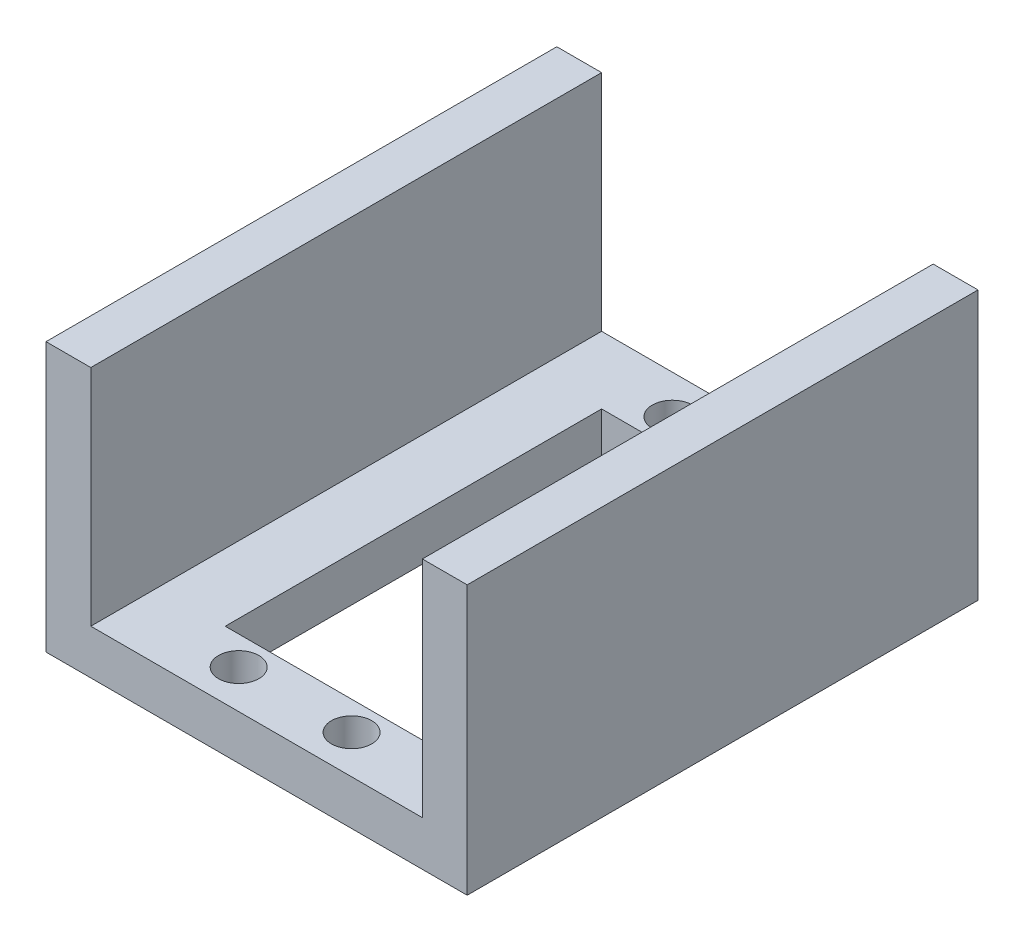
SolidWorks part; units mm, degrees
ref_plane "Front Plane" through (0, 0, 0) normal (0, 0, 1) x (1, 0, 0)
ref_plane "Top Plane" through (0, 0, 0) normal (0, 1, 0) x (1, 0, 0)
ref_plane "Right Plane" through (0, 0, 0) normal (1, 0, 0) x (0, 0, -1)
sketch "Sketch1" plane through (0, 0, 0) normal (0, 1, 0) x (1, 0, 0)
  line L0 (-18.5, -28.5) -> (-18.5, 28.5)
  line L1 (-11, -21) -> (11, -21)
  line L2 (-11, -21) -> (-11, 21)
  line L3 (-11, 21) -> (11, 21)
  line L4 (11, -21) -> (11, 21)
  line L5 (-11, -21) -> (11, 21) construction
  line L6 (-11, 21) -> (11, -21) construction
  line L7 (-18.5, 28.5) -> (18.5, 28.5)
  line L8 (18.5, -28.5) -> (18.5, 28.5)
  line L9 (-18.5, -28.5) -> (18.5, -28.5)
  point P0 (0, 0)
  dimension "D1" = 22
  dimension "D2" = 42
  dimension "D3" = 7.5
extrude "Boss-Extrude1" add sketch "Sketch1" along normal blind 5
hole_wizard "M4 Clearance Hole1" positions "Sketch2" profile "Sketch3" hole size "M4" standard "ANSI Metric" end condition through all
sketch "Sketch2" plane through (0, 5, 0) normal (0, 1, 0) x (1, 0, 0)
  line L1 (-6.3, 24.2) -> (6.3, 24.2) construction
  line L2 (-6.3, 24.2) -> (-6.3, -24.2) construction
  line L3 (-6.3, -24.2) -> (6.3, -24.2) construction
  line L4 (6.3, 24.2) -> (6.3, -24.2) construction
  line L5 (0, 28.5) -> (0, -28.5) construction
  line L6 (18.5, 28.5) -> (-18.5, 28.5) construction
  line L7 (-18.5, -28.5) -> (18.5, -28.5) construction
  line L9 (-18.5, 0) -> (18.5, 0) construction
  line L10 (-18.5, 28.5) -> (-18.5, -28.5) construction
  line L11 (18.5, -28.5) -> (18.5, 28.5) construction
  point P0 (-6.3, 24.2)
  point P2 (6.3, 24.2)
  point P4 (-6.3, -24.2)
  point P5 (6.3, -24.2)
  point P71 (0, 24.2)
  point P79 (-6.3, 0)
  dimension "D1" = 12.6
  dimension "D2" = 48.4
sketch "Sketch3" plane through (-6.3, 5, -24.2) normal (1, 0, 0) x (0, 0, 1)
  line L0 (0, 0) -> (0, 5)
  line L1 (0, 5) -> (2.25, 5)
  line L2 (2.25, 5) -> (2.25, 0)
  line L5 (2.25, 0) -> (0, 0)
  line L11 (0, -6.35) -> (0, 107.95) construction
  dimension "Thru Hole Dia." = 4.5
  dimension "Thru Hole Depth" = 5
sketch "Sketch4" plane through (0, 0, 0) normal (0, 1, 0) x (1, 0, 0)
  line L6 (-18.5, -28.5) -> (18.5, -28.5) construction
  line L7 (-18.5, 28.5) -> (-23.5, 28.5)
  line L8 (-18.5, 28.5) -> (-18.5, -28.5)
  line L9 (-18.5, -28.5) -> (-23.5, -28.5)
  line L10 (-23.5, 28.5) -> (-23.5, -28.5)
  line L11 (0, 28.5) -> (0, -28.5) construction
  line L12 (18.5, 28.5) -> (-18.5, 28.5) construction
  line L13 (18.5, -28.5) -> (23.5, -28.5)
  line L14 (23.5, 28.5) -> (23.5, -28.5)
  line L15 (18.5, 28.5) -> (23.5, 28.5)
  line L16 (18.5, 28.5) -> (18.5, -28.5)
  dimension "D1" = 5
extrude "Boss-Extrude2" add sketch "Sketch4" along normal blind 30
